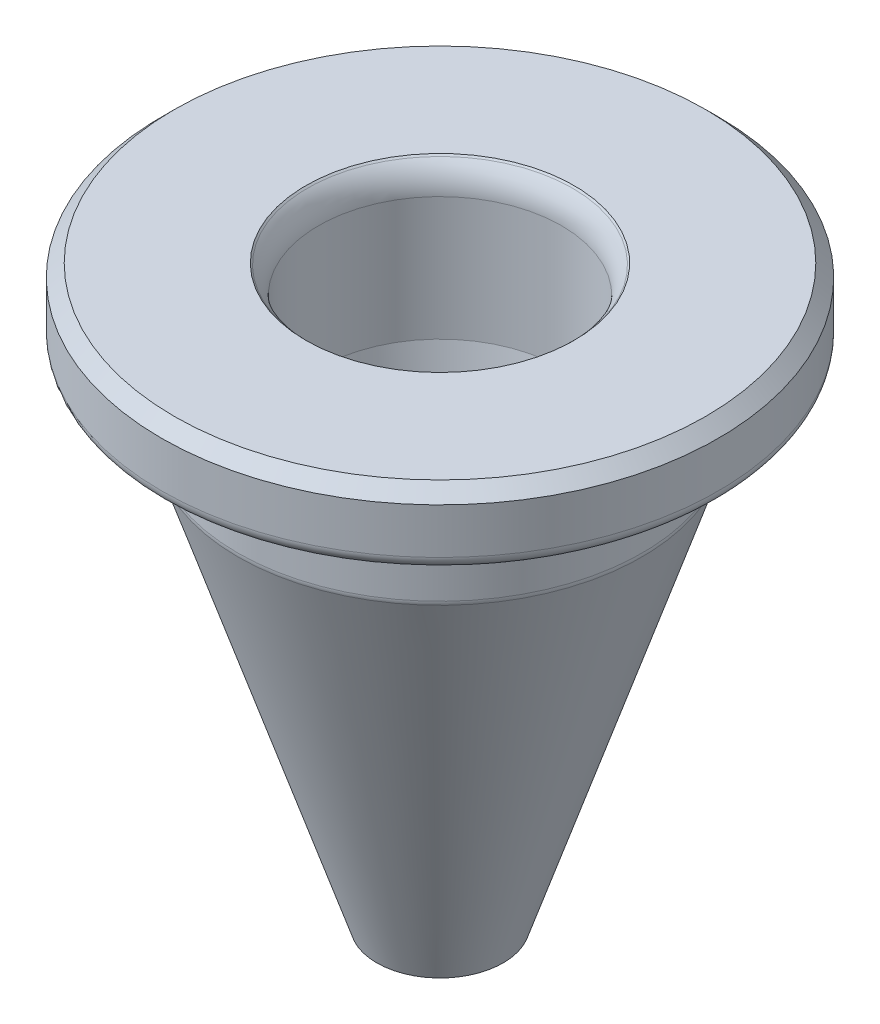
SolidWorks part; units mm, degrees
ref_plane "Ebene vorne" through (0, 0, 0) normal (0, 0, 1) x (1, 0, 0)
ref_plane "Ebene oben" through (0, 0, 0) normal (0, 1, 0) x (1, 0, 0)
ref_plane "Ebene rechts" through (0, 0, 0) normal (1, 0, 0) x (0, 0, -1)
sketch "Skizze1" plane through (0, 0, 0) normal (0, 0, 1) x (1, 0, 0)
  line L0 (0, 0) -> (0, 22) construction
  line L1 (2, 0) -> (4.8, 17)
  line L2 (4.8, 17) -> (4.8, 22)
  line L3 (4.8, 22) -> (8, 22)
  line L5 (8, 22) -> (8, 17)
  line L7 (2, 0) -> (2.5, 0.3)
  line L8 (2.5, 0.3) -> (8, 17)
  dimension "D1" = 9.6
  dimension "D2" = 22
  dimension "D3" = 5
  dimension "D4" = 4
  dimension "D5" = 16
  dimension "D6" = 0.5
  dimension "D7" = 0.3
revolve "Rotation1" add sketch "Skizze1" angle 360 about L0
other "Fläche verschieben1" face at (0, 22, -4.8) parameters "D1"=1
sketch "Skizze2" plane through (0, 23, 0) normal (0, 1, 0) x (1, 0, 0)
  circle A0 centre (0, 0) radius 11
  circle A1 centre (0, 0) radius 4.8
  dimension "D1" = 9.6
  dimension "D2" = 22
extrude "Aufsatz-Linear austragen1" add sketch "Skizze2" against normal blind 2.8
fillet "Verrundung1" radius 0.5 3 edges at (0, 20.2, 11) (0, 20.2, 8) (0, 17, -8)
ref_plane "Ebene1" through (0, 0, 0) normal (0, 0, 1) x (1, 0, 0)
chamfer "Fase1" distance 0.5 angle 45 2 edges at (0, 23, 11) (0, 23, 4.8)
fillet "Verrundung2" radius 1.5 1 edges at (0, 22.5, 4.8)
